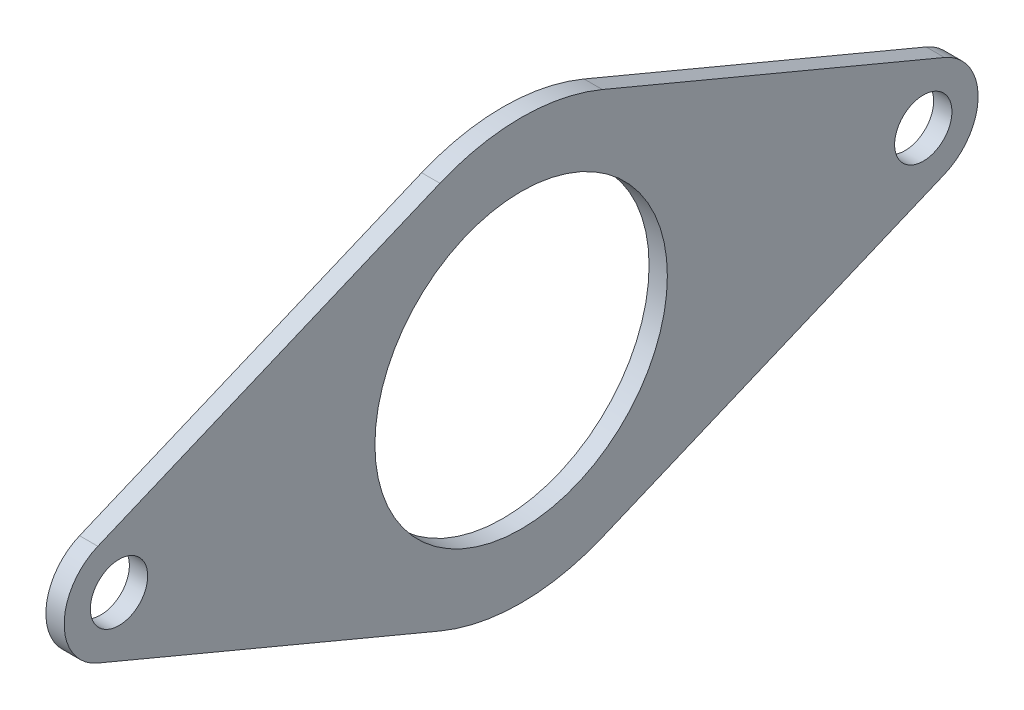
SolidWorks part; units mm, degrees
material "6061-T6 (SS)"
ref_plane "Front Plane" through (0, 0, 0) normal (0, 0, 1) x (1, 0, 0)
ref_plane "Top Plane" through (0, 0, 0) normal (0, 1, 0) x (1, 0, 0)
ref_plane "Right Plane" through (0, 0, 0) normal (1, 0, 0) x (0, 0, -1)
sketch "Sketch1" plane through (0, 0, 0) normal (1, 0, 0) x (0, 0, -1)
  line L0 (34.925, 0) -> (-34.925, 0) construction
  line L1 (-36.7651, -4.3927) -> (-7.0536, -16.8386)
  line L3 (-36.7651, 4.3927) -> (-7.0536, 16.8386)
  line L4 (36.7651, 4.3927) -> (7.0536, 16.8386)
  line L5 (36.7651, -4.3927) -> (7.0536, -16.8386)
  circle A0 centre (0, 0) radius 12.7
  arc A1 (-7.0536, -16.8386) -> (7.0536, -16.8386) centre (0, 0) ccw
  circle A2 centre (34.925, 0) radius 2.4892
  circle A3 centre (-34.925, 0) radius 2.4892
  arc A4 (36.7651, -4.3927) -> (36.7651, 4.3927) centre (34.925, 0) ccw
  arc A5 (-36.7651, 4.3927) -> (-36.7651, -4.3927) centre (-34.925, 0) ccw
  arc A6 (7.0536, 16.8386) -> (-7.0536, 16.8386) centre (0, 0) ccw
  point P7 (0, 0)
  dimension "D1" = 25.4
  dimension "D2" = 36.5125
  dimension "D4" = 4.9784
  dimension "D5" = 9.525
  dimension "D3" = 69.85
extrude "Boss-Extrude1" add sketch "Sketch1" along normal mid plane 1.5875
